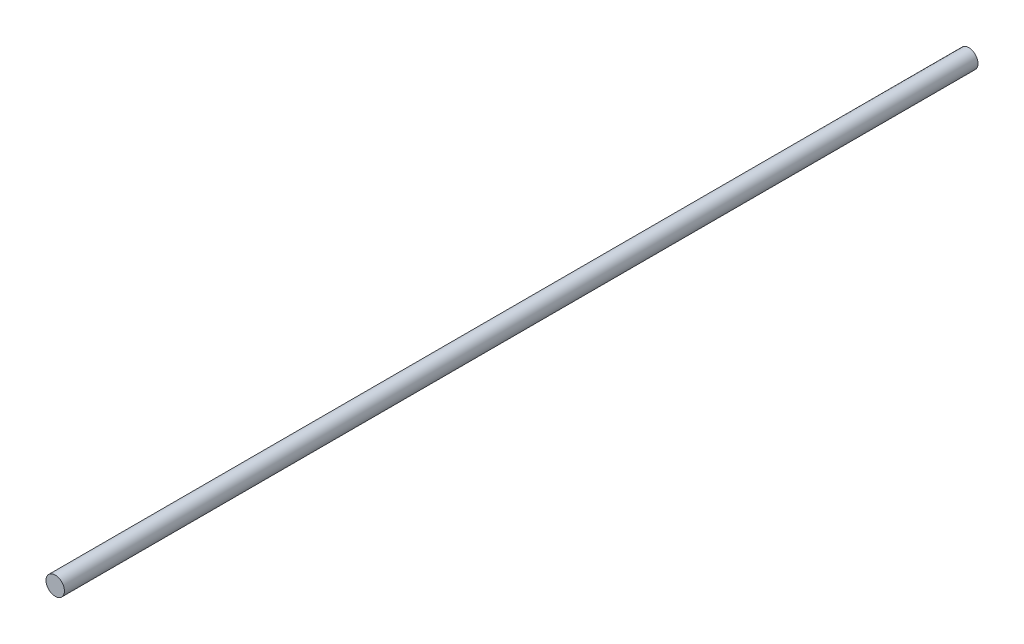
SolidWorks part; units mm, degrees
ref_plane "Front Plane" through (0, 0, 0) normal (0, 0, 1) x (1, 0, 0)
ref_plane "Top Plane" through (0, 0, 0) normal (0, 1, 0) x (1, 0, 0)
ref_plane "Right Plane" through (0, 0, 0) normal (1, 0, 0) x (0, 0, -1)
sketch "Sketch1" plane through (0, 0, 0) normal (0, 0, 1) x (1, 0, 0)
  circle A0 centre (0, 0) radius 4
  dimension "D1" = 8
extrude "Boss-Extrude1" add sketch "Sketch1" along normal mid plane 396
